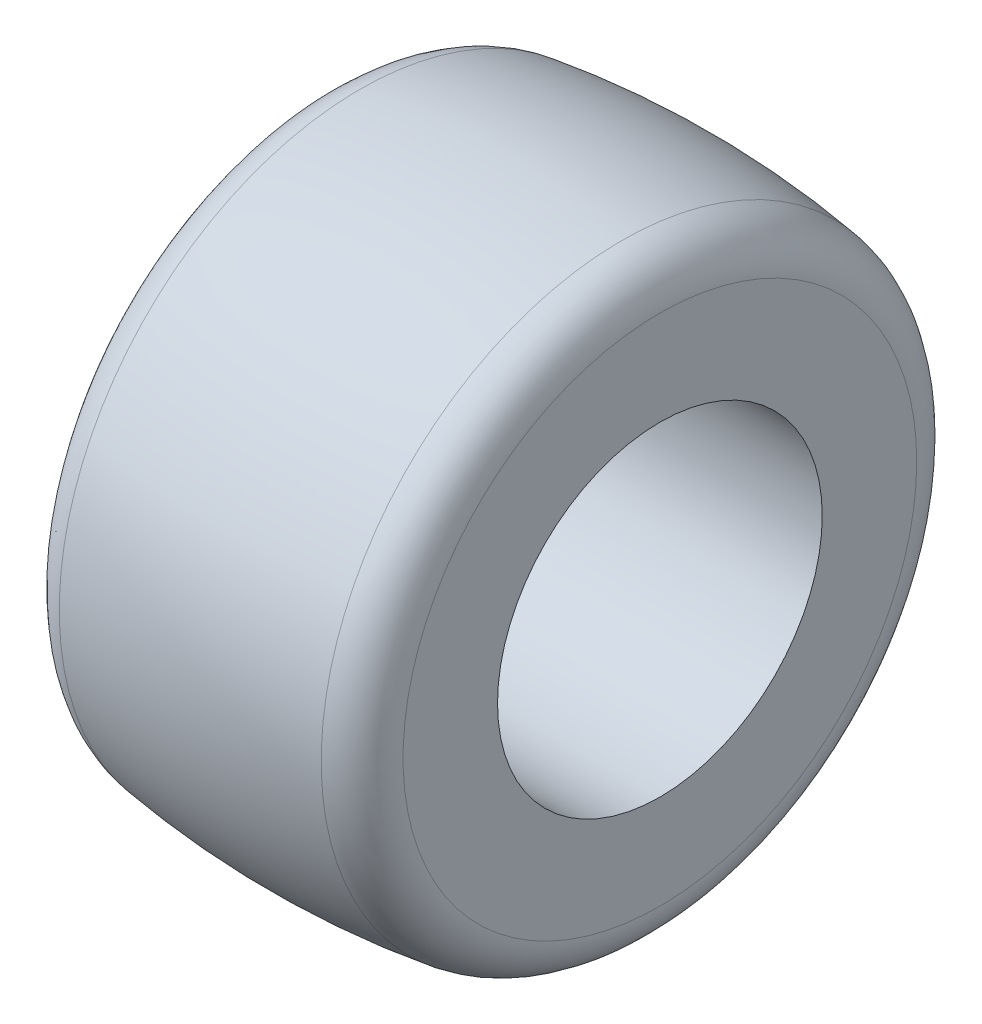
SolidWorks part; units mm, degrees
ref_plane "Front Plane" through (0, 0, 0) normal (0, 0, 1) x (1, 0, 0)
ref_plane "Top Plane" through (0, 0, 0) normal (0, 1, 0) x (1, 0, 0)
ref_plane "Right Plane" through (0, 0, 0) normal (1, 0, 0) x (0, 0, -1)
sketch "Sketch1" plane through (0, 0, 0) normal (0, 0, 1) x (1, 0, 0)
  line L0 (0, 0) -> (0, 17.4015)
  line L1 (22.9, 17.4015) -> (22.9, 0)
  line L2 (22.9, 0) -> (0, 0)
  arc A2 (2.5772, 20.3716) -> (20.3228, 20.3716) centre (11.45, -41.9548) cw
  arc A3 (0, 17.4015) -> (2.5772, 20.3716) centre (3, 17.4015) cw
  arc A4 (20.3228, 20.3716) -> (22.9, 17.4015) centre (19.9, 17.4015) cw
  point P2 (11.45, 21)
  point P3 (0, 0)
  point P6 (0, 0)
  point P11 (0, 19.95)
  point P14 (22.9, 19.95)
  dimension "D4" = 3
  dimension "D1" = 22.9
  dimension "D2" = 21
  dimension "D3" = 19.95
revolve "Revolve1" add sketch "Sketch1" angle 360 about L2
sketch "Sketch2" plane through (22.9, 0, 0) normal (1, 0, 0) x (0, 0, -1)
  circle A0 centre (0, 0) radius 11
  dimension "D1" = 22
extrude "Cut-Extrude1" cut sketch "Sketch2" against normal through all
